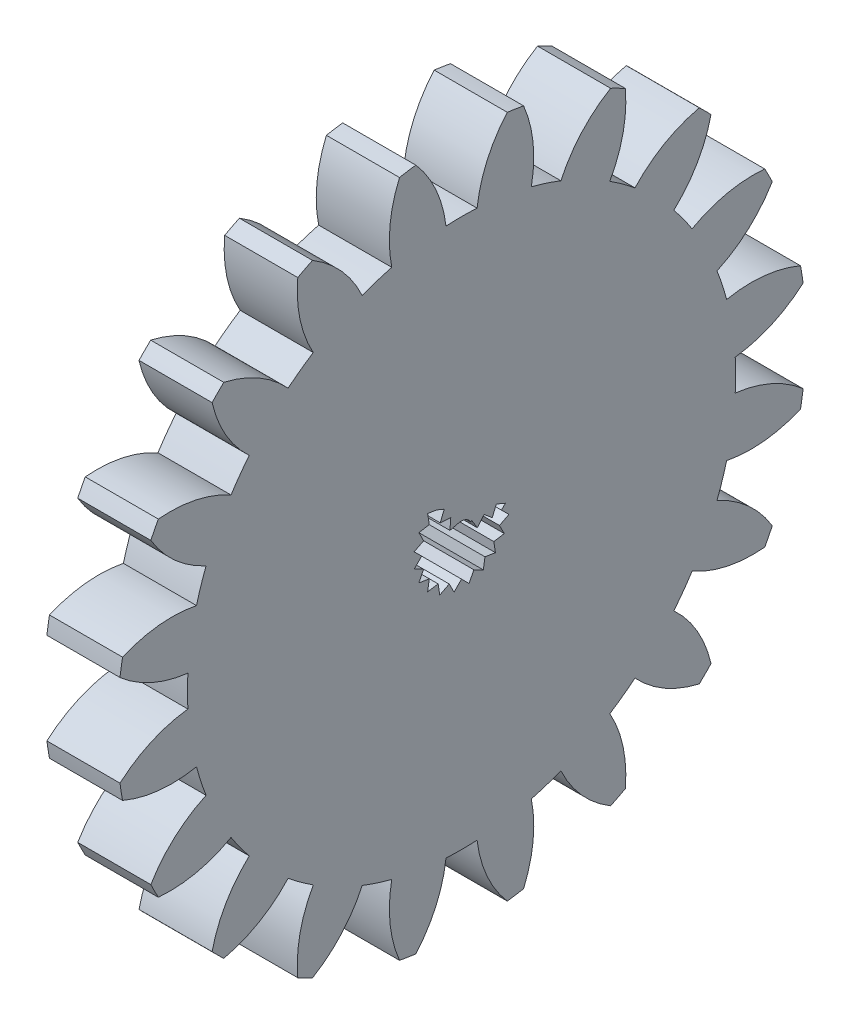
SolidWorks part; units mm, degrees
ref_plane "Plane1" through (0, 0, 0) normal (0, 0, 1) x (1, 0, 0)
ref_plane "Plane2" through (0, 0, 0) normal (0, 1, 0) x (1, 0, 0)
ref_plane "Plane3" through (0, 0, 0) normal (1, 0, 0) x (0, 0, -1)
other "Configuration Table"
sketch "HoldingSke" plane through (0, 0, 0) normal (0, 1, 0) x (1, 0, 0)
  line L0 (0, 0) -> (0.6265, -0.228)
  line L1 (-15, 0) -> (100, 0) construction
  line L2 (0, 0) -> (-2.1039, 2.3779)
  line L3 (0, 0) -> (-11.863, 4.5341)
  line L4 (0, 0) -> (8.1152, 2.9537)
  line L5 (0, 0) -> (-46.8476, -17.4728)
  line L6 (0, 0) -> (-2.9014, -1.9576)
  line L7 (-2.1039, 2.3779) -> (8.6586, 51.2059)
  line L8 (-76.2, 54.61) -> (-76.1, 54.61)
  line L9 (-71.009, 38.7566) -> (-53.1078, 45.2721)
  line L10 (-76.2, 71.12) -> (104.1128, 71.12)
  line L11 (0, 0) -> (-3.5, 0)
  line L12 (-76.2, 101.6) -> (-76.147, 101.6)
  line L13 (24.9733, 27.94) -> (52.9518, 28.4284)
  line L14 (24.9733, 27.94) -> (24.9743, 27.94)
  line L15 (24.9733, 27.94) -> (100.4006, 29.5858)
  line L16 (-63.627, -1.5) -> (-12.827, -1.5)
  circle A0 centre (0, 0) radius 0.5
  circle A1 centre (0, 0) radius 13.124
  circle A2 centre (0, 0) radius 37.5
  circle A3 centre (0, 0) radius 0.5
  dimension "MHD" = 26.248
  dimension "Hub_dia" = 75
  dimension "Bore" = 1
  dimension "MBD" = 1
  dimension "Num_teeth" = 20
  dimension "Pitch" = 0.6667
  dimension "Overall_len" = 50
  dimension "Show_teeth" = 20
  dimension "Thickness" = 3.5
  dimension "OAL" = 50.0001
  dimension "T_dim" = 0.1
  dimension "Ap" = 20
  dimension "H" = 19.05
  dimension "Pitch_radius" = 180.3128
  dimension "Width" = 3.5
  dimension "Backlash" = 0.053
  dimension "Addendum_fac" = 1
  dimension "Dedendum_fac" = 1.25
  dimension "Clearance_fac" = 0.25
  dimension "Dedendum_add" = 0.001
  dimension "Module" = 1.5
sketch "BasProSke" plane through (0, 0, 0) normal (0, 1, 0) x (1, 0, 0)
  line L0 (-10, 0) -> (60, 0) construction
  line L1 (0, 0) -> (0, 16.5)
  line L2 (0, 0) -> (3.5, 0)
  line L3 (3.5, 0) -> (3.5, 16.5)
  line L4 (3.5, 16.5) -> (0, 16.5)
  dimension "Thickness" = 3.5
  dimension "Diameter" = 33
revolve "Base-Revolve" add sketch "BasProSke" angle 360 about L0
sketch "TooCutSke" plane through (0, 0, 0) normal (1, 0, 0) x (0, 0, -1)
  line L1 (0, 0) -> (0, 107) construction
  line L2 (0, 0) -> (-1.2696, 14.9462) construction
  line L3 (0, 0) -> (-4.6808, 29.5532) construction
  line L4 (-1.2696, 14.9462) -> (-2.3404, 14.7766) construction
  arc A0 (0.7438, 13.1029) -> (-0.7438, 13.1029) centre (0, 0) ccw
  arc A1 (2.21, 16.377) -> (-2.21, 16.377) centre (0, 0) ccw
  circle A2 centre (0, 0) radius 15 construction
  circle A3 centre (0, 0) radius 14.0954 construction
  arc A4 (-0.7438, 13.1029) -> (-2.21, 16.377) centre (-6.7025, 12.3999) ccw
  arc A5 (2.21, 16.377) -> (0.7438, 13.1029) centre (6.7025, 12.3999) ccw
  dimension "Root_dia" = 26.248
  dimension "Overcut_dia" = 33.0508
  dimension "Pitch_dia" = 30
  dimension "Base_dia" = 28.1908
  dimension "Flank_rad" = 6
  dimension "Half_ang" = 9
  dimension "Half_CT" = 1.0841
extrude "ToothCut" cut sketch "TooCutSke" along normal through all
fillet "Breaks" [suppressed] radius 0.03
fillet "RootFillets" [suppressed] radius 0.376
pattern_circular "TeethCuts" count 20 every 18 about axis through (-10, 0, 0) along (1, 0, 0) of "ToothCut", "RootFillets", "Breaks"
sketch "HubNeaOneSke" plane through (0, 0, 0) normal (-1, 0, 0) x (0, 0, 1)
  circle A0 centre (0, 0) radius 13.124
  dimension "Diameter" = 26.248
extrude "HubNearOne" [suppressed] add sketch "HubNeaOneSke" along normal blind 46.5001
sketch "HubNeaBotSke" plane through (0, 0, 0) normal (-1, 0, 0) x (0, 0, 1)
  circle A0 centre (0, 0) radius 13.124
  dimension "Diameter" = 26.248
extrude "HubNearBoth" [suppressed] add sketch "HubNeaBotSke" along normal blind 23.25
ref_plane "FarPln" through (3.5, 0, 0) normal (1, 0, 0) x (0, 0, -1)
sketch "HubFarSke" plane through (3.5, 0, 0) normal (1, 0, 0) x (0, 0, -1)
  circle A0 centre (0, 0) radius 13.124
  dimension "Diameter" = 26.248
extrude "HubFar" [suppressed] add sketch "HubFarSke" along normal blind 23.25
sketch "BorSke" plane through (0, 0, 0) normal (1, 0, 0) x (0, 0, -1)
  circle A0 centre (0, 0) radius 0.5
  dimension "Diameter" = 1
extrude "Bore" cut sketch "BorSke" along normal mid plane 100.0001
sketch "KeySke" plane through (0, 0, 0) normal (1, 0, 0) x (0, 0, -1)
  line L0 (-0.05, 0) -> (-0.05, 0.6)
  line L1 (-0.05, 0.6) -> (0.05, 0.6)
  line L2 (0.05, 0.6) -> (0.05, 0)
  line L3 (0, 0) -> (0, 34) construction
  line L4 (-0.05, 0) -> (0.05, 0)
  dimension "Offset" = 0.6
  dimension "Width" = 0.1
extrude "Keyway" [suppressed] cut sketch "KeySke" along normal mid plane 100.0001
pattern_circular "Keyway2" [suppressed] count 2 every 90 about axis through (-10, 0, 0) along (1, 0, 0)
sketch "Sketch1" plane through (0, 0, 0) normal (-1, 0, 0) x (0, 0, 1)
  line L0 (-1.4699, -0.0979) -> (-1.6647, 0.3712) construction
  line L1 (-1.6647, 0.3712) -> (-2.1338, 0.1764) construction
  line L2 (-2.1338, 0.1764) -> (-2.1741, 0.6828) construction
  line L3 (-2.1741, 0.6828) -> (-2.6805, 0.6424) construction
  line L4 (-2.6805, 0.6424) -> (-2.5624, 1.1365) construction
  line L5 (-2.5624, 1.1365) -> (-3.0564, 1.2546) construction
  line L6 (-3.0564, 1.2546) -> (-2.7914, 1.6879) construction
  line L7 (-2.7914, 1.6879) -> (-3.2247, 1.953) construction
  line L8 (-3.2247, 1.953) -> (-2.8388, 2.2832) construction
  line L9 (-2.8388, 2.2832) -> (-3.169, 2.6692) construction
  line L10 (-3.169, 2.6692) -> (-2.6999, 2.864) construction
  line L11 (-2.6999, 2.864) -> (-2.8947, 3.3331) construction
  line L12 (-2.8947, 3.3331) -> (-2.3883, 3.3734) construction
  line L13 (-2.3883, 3.3734) -> (-2.4287, 3.8797) construction
  line L14 (-2.4287, 3.8797) -> (-1.9346, 3.7616) construction
  line L15 (-1.9346, 3.7616) -> (-1.8165, 4.2556) construction
  line L16 (-1.8165, 4.2556) -> (-1.3832, 3.9906) construction
  line L17 (-1.3832, 3.9906) -> (-1.1181, 4.424) construction
  line L18 (-1.1181, 4.424) -> (-0.7879, 4.038) construction
  line L19 (-0.7879, 4.038) -> (-0.402, 4.3682) construction
  line L20 (-0.402, 4.3682) -> (-0.2071, 3.8991) construction
  line L21 (-0.2071, 3.8991) -> (0.262, 4.0939) construction
  line L22 (0.262, 4.0939) -> (0.3023, 3.5876) construction
  line L23 (0.3023, 3.5876) -> (0.8086, 3.6279) construction
  line L24 (0.8086, 3.6279) -> (0.6905, 3.1339) construction
  line L25 (0.6905, 3.1339) -> (1.1845, 3.0157) construction
  line L26 (1.1845, 3.0157) -> (0.9195, 2.5824) construction
  line L27 (0.9195, 2.5824) -> (1.3529, 2.3174) construction
  line L28 (1.3529, 2.3174) -> (0.9669, 1.9871) construction
  line L29 (0.9669, 1.9871) -> (1.2971, 1.6012) construction
  line L30 (1.2971, 1.6012) -> (0.828, 1.4064) construction
  line L31 (0.828, 1.4064) -> (1.0228, 0.9373) construction
  line L32 (1.0228, 0.9373) -> (0.5165, 0.897) construction
  line L33 (0.5165, 0.897) -> (0.5568, 0.3906) construction
  line L34 (0.5568, 0.3906) -> (0.0628, 0.5087) construction
  line L35 (0.0628, 0.5087) -> (-0.0554, 0.0147) construction
  line L36 (-0.0554, 0.0147) -> (-0.4887, 0.2797) construction
  line L37 (-0.4887, 0.2797) -> (-0.7537, -0.1536) construction
  line L38 (-0.7537, -0.1536) -> (-1.084, 0.2323) construction
  line L39 (-1.084, 0.2323) -> (-1.4699, -0.0979) construction
  line L40 (-1.4699, -0.0979) -> (-1.6647, 0.3712)
  line L41 (-1.6647, 0.3712) -> (-2.1338, 0.1764)
  line L42 (-2.1338, 0.1764) -> (-2.1741, 0.6828)
  line L43 (-2.1741, 0.6828) -> (-2.6805, 0.6424)
  line L44 (-2.6805, 0.6424) -> (-2.5624, 1.1365)
  line L45 (-2.5624, 1.1365) -> (-3.0564, 1.2546)
  line L46 (-3.0564, 1.2546) -> (-2.7914, 1.6879)
  line L47 (-2.7914, 1.6879) -> (-3.2247, 1.953)
  line L48 (-3.2247, 1.953) -> (-2.8388, 2.2832)
  line L49 (-2.8388, 2.2832) -> (-3.169, 2.6692)
  line L50 (-3.169, 2.6692) -> (-2.6999, 2.864)
  line L51 (-2.6999, 2.864) -> (-2.8947, 3.3331)
  line L52 (-2.8947, 3.3331) -> (-2.3883, 3.3734)
  line L53 (-2.3883, 3.3734) -> (-2.4287, 3.8797)
  line L54 (-2.4287, 3.8797) -> (-1.9346, 3.7616)
  line L55 (-1.9346, 3.7616) -> (-1.8165, 4.2556)
  line L56 (-1.8165, 4.2556) -> (-1.3832, 3.9906)
  line L57 (-1.3832, 3.9906) -> (-1.1181, 4.424)
  line L58 (-1.1181, 4.424) -> (-0.7879, 4.038)
  line L59 (-0.7879, 4.038) -> (-0.402, 4.3682)
  line L60 (-0.402, 4.3682) -> (-0.2071, 3.8991)
  line L61 (-0.2071, 3.8991) -> (0.262, 4.0939)
  line L62 (0.262, 4.0939) -> (0.3023, 3.5876)
  line L63 (0.3023, 3.5876) -> (0.8086, 3.6279)
  line L64 (0.8086, 3.6279) -> (0.6905, 3.1339)
  line L65 (0.6905, 3.1339) -> (1.1845, 3.0157)
  line L66 (1.1845, 3.0157) -> (0.9195, 2.5824)
  line L67 (0.9195, 2.5824) -> (1.3529, 2.3174)
  line L68 (1.3529, 2.3174) -> (0.9669, 1.9871)
  line L69 (0.9669, 1.9871) -> (1.2971, 1.6012)
  line L70 (1.2971, 1.6012) -> (0.828, 1.4064)
  line L71 (0.828, 1.4064) -> (1.0228, 0.9373)
  line L72 (1.0228, 0.9373) -> (0.5165, 0.897)
  line L73 (0.5165, 0.897) -> (0.5568, 0.3906)
  line L74 (0.5568, 0.3906) -> (0.0628, 0.5087)
  line L75 (0.0628, 0.5087) -> (-0.0554, 0.0147)
  line L76 (-0.0554, 0.0147) -> (-0.4887, 0.2797)
  line L77 (-0.4887, 0.2797) -> (-0.7537, -0.1536)
  line L78 (-0.7537, -0.1536) -> (-1.084, 0.2323)
  line L79 (-1.084, 0.2323) -> (-1.4699, -0.0979)
  line L80 (2.2678, -0.3592) -> (1.9086, 0)
  line L81 (1.9086, 0) -> (2.2678, 0.3592)
  line L82 (2.2678, 0.3592) -> (1.8152, 0.5898)
  line L83 (1.8152, 0.5898) -> (2.0458, 1.0424)
  line L84 (2.0458, 1.0424) -> (1.5441, 1.1218)
  line L85 (1.5441, 1.1218) -> (1.6235, 1.6235)
  line L86 (1.6235, 1.6235) -> (1.1218, 1.5441)
  line L87 (1.1218, 1.5441) -> (1.0424, 2.0458)
  line L88 (1.0424, 2.0458) -> (0.5898, 1.8152)
  line L89 (0.5898, 1.8152) -> (0.3592, 2.2678)
  line L90 (0.3592, 2.2678) -> (0, 1.9086)
  line L91 (0, 1.9086) -> (-0.3592, 2.2678)
  line L92 (-0.3592, 2.2678) -> (-0.5898, 1.8152)
  line L93 (-0.5898, 1.8152) -> (-1.0424, 2.0458)
  line L94 (-1.0424, 2.0458) -> (-1.1218, 1.5441)
  line L95 (-1.1218, 1.5441) -> (-1.6235, 1.6235)
  line L96 (-1.6235, 1.6235) -> (-1.5441, 1.1218)
  line L97 (-1.5441, 1.1218) -> (-2.0458, 1.0424)
  line L98 (-2.0458, 1.0424) -> (-1.8152, 0.5898)
  line L99 (-1.8152, 0.5898) -> (-2.2678, 0.3592)
  line L100 (-2.2678, 0.3592) -> (-1.9086, 0)
  line L101 (-1.9086, 0) -> (-2.2678, -0.3592)
  line L102 (-2.2678, -0.3592) -> (-1.8152, -0.5898)
  line L103 (-1.8152, -0.5898) -> (-2.0458, -1.0424)
  line L104 (-2.0458, -1.0424) -> (-1.5441, -1.1218)
  line L105 (-1.5441, -1.1218) -> (-1.6235, -1.6235)
  line L106 (-1.6235, -1.6235) -> (-1.1218, -1.5441)
  line L107 (-1.1218, -1.5441) -> (-1.0424, -2.0458)
  line L108 (-1.0424, -2.0458) -> (-0.5898, -1.8152)
  line L109 (-0.5898, -1.8152) -> (-0.3592, -2.2678)
  line L110 (-0.3592, -2.2678) -> (0, -1.9086)
  line L111 (0, -1.9086) -> (0.3592, -2.2678)
  line L112 (0.3592, -2.2678) -> (0.5898, -1.8152)
  line L113 (0.5898, -1.8152) -> (1.0424, -2.0458)
  line L114 (1.0424, -2.0458) -> (1.1218, -1.5441)
  line L115 (1.1218, -1.5441) -> (1.6235, -1.6235)
  line L116 (1.6235, -1.6235) -> (1.5441, -1.1218)
  line L117 (1.5441, -1.1218) -> (2.0458, -1.0424)
  line L118 (2.0458, -1.0424) -> (1.8152, -0.5898)
  line L119 (1.8152, -0.5898) -> (2.2678, -0.3592)
  arc A0 (13.1029, 0.7438) -> (16.354, 2.1898) centre (12.3999, 6.7025) ccw construction
  arc A1 (16.354, 2.1898) -> (16.2303, 2.9711) centre (0, 0) ccw construction
  arc A2 (16.2303, 2.9711) -> (12.6915, 3.3416) centre (13.8642, -2.5427) ccw construction
  arc A3 (12.6915, 3.3416) -> (12.2318, 4.7564) centre (0, 0) ccw construction
  arc A4 (12.2318, 4.7564) -> (14.8769, 7.1363) centre (9.7218, 10.2062) ccw construction
  arc A5 (14.8769, 7.1363) -> (14.5178, 7.8411) centre (0, 0) ccw construction
  arc A6 (14.5178, 7.8411) -> (11.0377, 7.0999) centre (13.9713, 1.866) ccw construction
  arc A7 (11.0377, 7.0999) -> (10.1633, 8.3035) centre (0, 0) ccw construction
  arc A8 (10.1633, 8.3035) -> (11.9436, 11.3842) centre (6.0921, 12.7109) ccw construction
  arc A9 (11.9436, 11.3842) -> (11.3842, 11.9436) centre (0, 0) ccw construction
  arc A10 (11.3842, 11.9436) -> (8.3035, 10.1633) centre (12.7109, 6.0921) ccw construction
  arc A11 (8.3035, 10.1633) -> (7.0999, 11.0377) centre (0, 0) ccw construction
  arc A12 (7.0999, 11.0377) -> (7.8411, 14.5178) centre (1.866, 13.9713) ccw construction
  arc A13 (7.8411, 14.5178) -> (7.1363, 14.8769) centre (0, 0) ccw construction
  arc A14 (7.1363, 14.8769) -> (4.7564, 12.2318) centre (10.2062, 9.7218) ccw construction
  arc A15 (4.7564, 12.2318) -> (3.3416, 12.6915) centre (0, 0) ccw construction
  arc A16 (3.3416, 12.6915) -> (2.9711, 16.2303) centre (-2.5427, 13.8642) ccw construction
  arc A17 (2.9711, 16.2303) -> (2.1898, 16.354) centre (0, 0) ccw construction
  arc A18 (2.1898, 16.354) -> (0.7438, 13.1029) centre (6.7025, 12.3999) ccw construction
  arc A19 (0.7438, 13.1029) -> (-0.7438, 13.1029) centre (0, 0) ccw construction
  arc A20 (-0.7438, 13.1029) -> (-2.1898, 16.354) centre (-6.7025, 12.3999) ccw construction
  arc A21 (-2.1898, 16.354) -> (-2.9711, 16.2303) centre (0, 0) ccw construction
  arc A22 (-2.9711, 16.2303) -> (-3.3416, 12.6915) centre (2.5427, 13.8642) ccw construction
  arc A23 (-3.3416, 12.6915) -> (-4.7564, 12.2318) centre (0, 0) ccw construction
  arc A24 (-4.7564, 12.2318) -> (-7.1363, 14.8769) centre (-10.2062, 9.7218) ccw construction
  arc A25 (-7.1363, 14.8769) -> (-7.8411, 14.5178) centre (0, 0) ccw construction
  arc A26 (-7.8411, 14.5178) -> (-7.0999, 11.0377) centre (-1.866, 13.9713) ccw construction
  arc A27 (-7.0999, 11.0377) -> (-8.3035, 10.1633) centre (0, 0) ccw construction
  arc A28 (-8.3035, 10.1633) -> (-11.3842, 11.9436) centre (-12.7109, 6.0921) ccw construction
  arc A29 (-11.3842, 11.9436) -> (-11.9436, 11.3842) centre (0, 0) ccw construction
  arc A30 (-11.9436, 11.3842) -> (-10.1633, 8.3035) centre (-6.0921, 12.7109) ccw construction
  arc A31 (-10.1633, 8.3035) -> (-11.0377, 7.0999) centre (0, 0) ccw construction
  arc A32 (-11.0377, 7.0999) -> (-14.5178, 7.8411) centre (-13.9713, 1.866) ccw construction
  arc A33 (-14.5178, 7.8411) -> (-14.8769, 7.1363) centre (0, 0) ccw construction
  arc A34 (-14.8769, 7.1363) -> (-12.2318, 4.7564) centre (-9.7218, 10.2062) ccw construction
  arc A35 (-12.2318, 4.7564) -> (-12.6915, 3.3416) centre (0, 0) ccw construction
  arc A36 (-12.6915, 3.3416) -> (-16.2303, 2.9711) centre (-13.8642, -2.5427) ccw construction
  arc A37 (-16.2303, 2.9711) -> (-16.354, 2.1898) centre (0, 0) ccw construction
  arc A38 (-16.354, 2.1898) -> (-13.1029, 0.7438) centre (-12.3999, 6.7025) ccw construction
  arc A39 (-13.1029, 0.7438) -> (-13.1029, -0.7438) centre (0, 0) ccw construction
  arc A40 (-13.1029, -0.7438) -> (-16.354, -2.1898) centre (-12.3999, -6.7025) ccw construction
  arc A41 (-16.354, -2.1898) -> (-16.2303, -2.9711) centre (0, 0) ccw construction
  arc A42 (-16.2303, -2.9711) -> (-12.6915, -3.3416) centre (-13.8642, 2.5427) ccw construction
  arc A43 (-12.6915, -3.3416) -> (-12.2318, -4.7564) centre (0, 0) ccw construction
  arc A44 (-12.2318, -4.7564) -> (-14.8769, -7.1363) centre (-9.7218, -10.2062) ccw construction
  arc A45 (-14.8769, -7.1363) -> (-14.5178, -7.8411) centre (0, 0) ccw construction
  arc A46 (-14.5178, -7.8411) -> (-11.0377, -7.0999) centre (-13.9713, -1.866) ccw construction
  arc A47 (-11.0377, -7.0999) -> (-10.1633, -8.3035) centre (0, 0) ccw construction
  arc A48 (-10.1633, -8.3035) -> (-11.9436, -11.3842) centre (-6.0921, -12.7109) ccw construction
  arc A49 (-11.9436, -11.3842) -> (-11.3842, -11.9436) centre (0, 0) ccw construction
  arc A50 (-11.3842, -11.9436) -> (-8.3035, -10.1633) centre (-12.7109, -6.0921) ccw construction
  arc A51 (-8.3035, -10.1633) -> (-7.0999, -11.0377) centre (0, 0) ccw construction
  arc A52 (-7.0999, -11.0377) -> (-7.8411, -14.5178) centre (-1.866, -13.9713) ccw construction
  arc A53 (-7.8411, -14.5178) -> (-7.1363, -14.8769) centre (0, 0) ccw construction
  arc A54 (-7.1363, -14.8769) -> (-4.7564, -12.2318) centre (-10.2062, -9.7218) ccw construction
  arc A55 (-4.7564, -12.2318) -> (-3.3416, -12.6915) centre (0, 0) ccw construction
  arc A56 (-3.3416, -12.6915) -> (-2.9711, -16.2303) centre (2.5427, -13.8642) ccw construction
  arc A57 (-2.9711, -16.2303) -> (-2.1898, -16.354) centre (0, 0) ccw construction
  arc A58 (-2.1898, -16.354) -> (-0.7438, -13.1029) centre (-6.7025, -12.3999) ccw construction
  arc A59 (-0.7438, -13.1029) -> (0.7438, -13.1029) centre (0, 0) ccw construction
  arc A60 (0.7438, -13.1029) -> (2.1898, -16.354) centre (6.7025, -12.3999) ccw construction
  arc A61 (2.1898, -16.354) -> (2.9711, -16.2303) centre (0, 0) ccw construction
  arc A62 (2.9711, -16.2303) -> (3.3416, -12.6915) centre (-2.5427, -13.8642) ccw construction
  arc A63 (3.3416, -12.6915) -> (4.7564, -12.2318) centre (0, 0) ccw construction
  arc A64 (4.7564, -12.2318) -> (7.1363, -14.8769) centre (10.2062, -9.7218) ccw construction
  arc A65 (7.1363, -14.8769) -> (7.8411, -14.5178) centre (0, 0) ccw construction
  arc A66 (7.8411, -14.5178) -> (7.0999, -11.0377) centre (1.866, -13.9713) ccw construction
  arc A67 (7.0999, -11.0377) -> (8.3035, -10.1633) centre (0, 0) ccw construction
  arc A68 (8.3035, -10.1633) -> (11.3842, -11.9436) centre (12.7109, -6.0921) ccw construction
  arc A69 (11.3842, -11.9436) -> (11.9436, -11.3842) centre (0, 0) ccw construction
  arc A70 (11.9436, -11.3842) -> (10.1633, -8.3035) centre (6.0921, -12.7109) ccw construction
  arc A71 (10.1633, -8.3035) -> (11.0377, -7.0999) centre (0, 0) ccw construction
  arc A72 (11.0377, -7.0999) -> (14.5178, -7.8411) centre (13.9713, -1.866) ccw construction
  arc A73 (14.5178, -7.8411) -> (14.8769, -7.1363) centre (0, 0) ccw construction
  arc A74 (14.8769, -7.1363) -> (12.2318, -4.7564) centre (9.7218, -10.2062) ccw construction
  arc A75 (12.2318, -4.7564) -> (12.6915, -3.3416) centre (0, 0) ccw construction
  arc A76 (12.6915, -3.3416) -> (16.2303, -2.9711) centre (13.8642, 2.5427) ccw construction
  arc A77 (16.2303, -2.9711) -> (16.354, -2.1898) centre (0, 0) ccw construction
  arc A78 (16.354, -2.1898) -> (13.1029, -0.7438) centre (12.3999, -6.7025) ccw construction
  arc A79 (13.1029, -0.7438) -> (13.1029, 0.7438) centre (0, 0) ccw construction
  arc A80 (13.1029, 0.7438) -> (16.354, 2.1898) centre (12.3999, 6.7025) ccw
  arc A81 (16.354, 2.1898) -> (16.2303, 2.9711) centre (0, 0) ccw
  arc A82 (16.2303, 2.9711) -> (12.6915, 3.3416) centre (13.8642, -2.5427) ccw
  arc A83 (12.6915, 3.3416) -> (12.2318, 4.7564) centre (0, 0) ccw
  arc A84 (12.2318, 4.7564) -> (14.8769, 7.1363) centre (9.7218, 10.2062) ccw
  arc A85 (14.8769, 7.1363) -> (14.5178, 7.8411) centre (0, 0) ccw
  arc A86 (14.5178, 7.8411) -> (11.0377, 7.0999) centre (13.9713, 1.866) ccw
  arc A87 (11.0377, 7.0999) -> (10.1633, 8.3035) centre (0, 0) ccw
  arc A88 (10.1633, 8.3035) -> (11.9436, 11.3842) centre (6.0921, 12.7109) ccw
  arc A89 (11.9436, 11.3842) -> (11.3842, 11.9436) centre (0, 0) ccw
  arc A90 (11.3842, 11.9436) -> (8.3035, 10.1633) centre (12.7109, 6.0921) ccw
  arc A91 (8.3035, 10.1633) -> (7.0999, 11.0377) centre (0, 0) ccw
  arc A92 (7.0999, 11.0377) -> (7.8411, 14.5178) centre (1.866, 13.9713) ccw
  arc A93 (7.8411, 14.5178) -> (7.1363, 14.8769) centre (0, 0) ccw
  arc A94 (7.1363, 14.8769) -> (4.7564, 12.2318) centre (10.2062, 9.7218) ccw
  arc A95 (4.7564, 12.2318) -> (3.3416, 12.6915) centre (0, 0) ccw
  arc A96 (3.3416, 12.6915) -> (2.9711, 16.2303) centre (-2.5427, 13.8642) ccw
  arc A97 (2.9711, 16.2303) -> (2.1898, 16.354) centre (0, 0) ccw
  arc A98 (2.1898, 16.354) -> (0.7438, 13.1029) centre (6.7025, 12.3999) ccw
  arc A99 (0.7438, 13.1029) -> (-0.7438, 13.1029) centre (0, 0) ccw
  arc A100 (-0.7438, 13.1029) -> (-2.1898, 16.354) centre (-6.7025, 12.3999) ccw
  arc A101 (-2.1898, 16.354) -> (-2.9711, 16.2303) centre (0, 0) ccw
  arc A102 (-2.9711, 16.2303) -> (-3.3416, 12.6915) centre (2.5427, 13.8642) ccw
  arc A103 (-3.3416, 12.6915) -> (-4.7564, 12.2318) centre (0, 0) ccw
  arc A104 (-4.7564, 12.2318) -> (-7.1363, 14.8769) centre (-10.2062, 9.7218) ccw
  arc A105 (-7.1363, 14.8769) -> (-7.8411, 14.5178) centre (0, 0) ccw
  arc A106 (-7.8411, 14.5178) -> (-7.0999, 11.0377) centre (-1.866, 13.9713) ccw
  arc A107 (-7.0999, 11.0377) -> (-8.3035, 10.1633) centre (0, 0) ccw
  arc A108 (-8.3035, 10.1633) -> (-11.3842, 11.9436) centre (-12.7109, 6.0921) ccw
  arc A109 (-11.3842, 11.9436) -> (-11.9436, 11.3842) centre (0, 0) ccw
  arc A110 (-11.9436, 11.3842) -> (-10.1633, 8.3035) centre (-6.0921, 12.7109) ccw
  arc A111 (-10.1633, 8.3035) -> (-11.0377, 7.0999) centre (0, 0) ccw
  arc A112 (-11.0377, 7.0999) -> (-14.5178, 7.8411) centre (-13.9713, 1.866) ccw
  arc A113 (-14.5178, 7.8411) -> (-14.8769, 7.1363) centre (0, 0) ccw
  arc A114 (-14.8769, 7.1363) -> (-12.2318, 4.7564) centre (-9.7218, 10.2062) ccw
  arc A115 (-12.2318, 4.7564) -> (-12.6915, 3.3416) centre (0, 0) ccw
  arc A116 (-12.6915, 3.3416) -> (-16.2303, 2.9711) centre (-13.8642, -2.5427) ccw
  arc A117 (-16.2303, 2.9711) -> (-16.354, 2.1898) centre (0, 0) ccw
  arc A118 (-16.354, 2.1898) -> (-13.1029, 0.7438) centre (-12.3999, 6.7025) ccw
  arc A119 (-13.1029, 0.7438) -> (-13.1029, -0.7438) centre (0, 0) ccw
  arc A120 (-13.1029, -0.7438) -> (-16.354, -2.1898) centre (-12.3999, -6.7025) ccw
  arc A121 (-16.354, -2.1898) -> (-16.2303, -2.9711) centre (0, 0) ccw
  arc A122 (-16.2303, -2.9711) -> (-12.6915, -3.3416) centre (-13.8642, 2.5427) ccw
  arc A123 (-12.6915, -3.3416) -> (-12.2318, -4.7564) centre (0, 0) ccw
  arc A124 (-12.2318, -4.7564) -> (-14.8769, -7.1363) centre (-9.7218, -10.2062) ccw
  arc A125 (-14.8769, -7.1363) -> (-14.5178, -7.8411) centre (0, 0) ccw
  arc A126 (-14.5178, -7.8411) -> (-11.0377, -7.0999) centre (-13.9713, -1.866) ccw
  arc A127 (-11.0377, -7.0999) -> (-10.1633, -8.3035) centre (0, 0) ccw
  arc A128 (-10.1633, -8.3035) -> (-11.9436, -11.3842) centre (-6.0921, -12.7109) ccw
  arc A129 (-11.9436, -11.3842) -> (-11.3842, -11.9436) centre (0, 0) ccw
  arc A130 (-11.3842, -11.9436) -> (-8.3035, -10.1633) centre (-12.7109, -6.0921) ccw
  arc A131 (-8.3035, -10.1633) -> (-7.0999, -11.0377) centre (0, 0) ccw
  arc A132 (-7.0999, -11.0377) -> (-7.8411, -14.5178) centre (-1.866, -13.9713) ccw
  arc A133 (-7.8411, -14.5178) -> (-7.1363, -14.8769) centre (0, 0) ccw
  arc A134 (-7.1363, -14.8769) -> (-4.7564, -12.2318) centre (-10.2062, -9.7218) ccw
  arc A135 (-4.7564, -12.2318) -> (-3.3416, -12.6915) centre (0, 0) ccw
  arc A136 (-3.3416, -12.6915) -> (-2.9711, -16.2303) centre (2.5427, -13.8642) ccw
  arc A137 (-2.9711, -16.2303) -> (-2.1898, -16.354) centre (0, 0) ccw
  arc A138 (-2.1898, -16.354) -> (-0.7438, -13.1029) centre (-6.7025, -12.3999) ccw
  arc A139 (-0.7438, -13.1029) -> (0.7438, -13.1029) centre (0, 0) ccw
  arc A140 (0.7438, -13.1029) -> (2.1898, -16.354) centre (6.7025, -12.3999) ccw
  arc A141 (2.1898, -16.354) -> (2.9711, -16.2303) centre (0, 0) ccw
  arc A142 (2.9711, -16.2303) -> (3.3416, -12.6915) centre (-2.5427, -13.8642) ccw
  arc A143 (3.3416, -12.6915) -> (4.7564, -12.2318) centre (0, 0) ccw
  arc A144 (4.7564, -12.2318) -> (7.1363, -14.8769) centre (10.2062, -9.7218) ccw
  arc A145 (7.1363, -14.8769) -> (7.8411, -14.5178) centre (0, 0) ccw
  arc A146 (7.8411, -14.5178) -> (7.0999, -11.0377) centre (1.866, -13.9713) ccw
  arc A147 (7.0999, -11.0377) -> (8.3035, -10.1633) centre (0, 0) ccw
  arc A148 (8.3035, -10.1633) -> (11.3842, -11.9436) centre (12.7109, -6.0921) ccw
  arc A149 (11.3842, -11.9436) -> (11.9436, -11.3842) centre (0, 0) ccw
  arc A150 (11.9436, -11.3842) -> (10.1633, -8.3035) centre (6.0921, -12.7109) ccw
  arc A151 (10.1633, -8.3035) -> (11.0377, -7.0999) centre (0, 0) ccw
  arc A152 (11.0377, -7.0999) -> (14.5178, -7.8411) centre (13.9713, -1.866) ccw
  arc A153 (14.5178, -7.8411) -> (14.8769, -7.1363) centre (0, 0) ccw
  arc A154 (14.8769, -7.1363) -> (12.2318, -4.7564) centre (9.7218, -10.2062) ccw
  arc A155 (12.2318, -4.7564) -> (12.6915, -3.3416) centre (0, 0) ccw
  arc A156 (12.6915, -3.3416) -> (16.2303, -2.9711) centre (13.8642, 2.5427) ccw
  arc A157 (16.2303, -2.9711) -> (16.354, -2.1898) centre (0, 0) ccw
  arc A158 (16.354, -2.1898) -> (13.1029, -0.7438) centre (12.3999, -6.7025) ccw
  arc A159 (13.1029, -0.7438) -> (13.1029, 0.7438) centre (0, 0) ccw
  circle A160 centre (0, 0) radius 2.296
  point P159 (0, 0)
  point P162 (0, 0)
  point P163 (0, 0)
  point P164 (0, 0)
extrude "Cut-Extrude1" cut sketch "Sketch1" against normal blind 10 contours L118 L119 L80 L81 L82 L83 L84 L85 L86 L87 L88 L89 L90 L91 L92 L93 L94 L95 L96 L97 L98 L99 L100 L101 L102 L103 L104 L105 L106 L107 L108 L109 L110 L111 L112 L113 L114 L115 L116 L117
equation "' \"Module@HoldingSke\" = 6.35"
equation "' \"Num_teeth@HoldingSke\" = 12"
equation "' \"Ap@HoldingSke\" =  20"
equation "' \"Ap@HoldingSke\" = 20"
equation "' \"Width@HoldingSke\" = 0.5 * 25.4"
equation "' \"Hub_dia@HoldingSke\"= 1 * 25.4"
equation "' \"Hub_dia@HoldingSke\" = 1 * 25.4"
equation "' \"Overall_len@HoldingSke\" = 1.0 * 25.4"
equation "' \"Bore@HoldingSke\" = 0.75 * 25.4"
equation "' \"T_dim@HoldingSke\" = 0.1 * 25.4"
equation "' \"Width@KeySke\" = 0.25 * 25.4"
equation "' \"Show_teeth@HoldingSke\" = 13"
equation "' \"Backlash@HoldingSke\" = 0.009 * 25.4"
equation "' \"Addendum_fac@HoldingSke\" = 1.0"
equation "' \"Dedendum_fac@HoldingSke\" = 1.25"
equation "' \"Dedendum_add@HoldingSke\" = 0.00005 * 25.4"
equation "' \"Clearance_fac@HoldingSke\" = 0.25"
equation "\"Pitch@HoldingSke\" = 1 / \"Module@HoldingSke\""
equation "\"Overcut_dia@TooCutSke\" = (\"Num_teeth@HoldingSke\" + 2 * \"Addendum_fac@HoldingSke\") / \"Pitch@HoldingSke\" + 0.002 * 25.4"
equation "\"Pitch_dia@TooCutSke\" = \"Num_teeth@HoldingSke\" / \"Pitch@HoldingSke\""
equation "\"Base_dia@TooCutSke\" = \"Num_teeth@HoldingSke\" / \"Pitch@HoldingSke\" * cos((\"Ap@HoldingSke\"  * 3.14159265 / 180))"
equation "\"Root_dia@TooCutSke\" = (\"Num_teeth@HoldingSke\" + 2) / \"Pitch@HoldingSke\" - 2 * (\"Addendum_fac@HoldingSke\" + \"Dedendum_fac@HoldingSke\") / \"Pitch@HoldingSke\" - \"Dedendum_add@HoldingSke\" * 2"
equation "\"Half_ang@TooCutSke\" = 180 / \"Num_teeth@HoldingSke\""
equation "\"Half_CT@TooCutSke\" = \"Num_teeth@HoldingSke\" / \"Pitch@HoldingSke\" * sin((3.14159265 / 2 / \"Num_teeth@HoldingSke\")) / 2 - 7 * \"Backlash@HoldingSke\" / 4"
equation "\"Flank_rad@TooCutSke\" = \"Num_teeth@HoldingSke\" / \"Pitch@HoldingSke\" / 5"
equation "\"Radius@RootFillets\" = \"Clearance_fac@HoldingSke\" / \"Pitch@HoldingSke\" + \"Dedendum_add@HoldingSke\""
equation "\"Break_rad@Breaks\" = 0.02 / \"Pitch@HoldingSke\""
equation "\"Thickness@HoldingSke\" = \"Width@HoldingSke\""
equation "\"OAL@HoldingSke\" = \"Thickness@HoldingSke\""
equation "\"MHD@HoldingSke\" = (\"Num_teeth@HoldingSke\" + 2) / \"Pitch@HoldingSke\" - 2 * (\"Addendum_fac@HoldingSke\" + \"Dedendum_fac@HoldingSke\")  / \"Pitch@HoldingSke\" - \"Dedendum_add@HoldingSke\" * 2"
equation "\"MBD@HoldingSke\" = (\"Num_teeth@HoldingSke\" + 2) / \"Pitch@HoldingSke\" - 2 * (\"Addendum_fac@HoldingSke\" + \"Dedendum_fac@HoldingSke\")  / \"Pitch@HoldingSke\" - \"Dedendum_add@HoldingSke\" * 2 - 0.002 * 25.4"
equation "\"MHD@HoldingSke\" = ((sgn( \"MHD@HoldingSke\" - \"Hub_dia@HoldingSke\" )-1)*( \"MHD@HoldingSke\" - \"Hub_dia@HoldingSke\" ))/-2+ \"Hub_dia@HoldingSke\""
equation "\"MBD@HoldingSke\" = ((sgn( \"MBD@HoldingSke\" - \"Bore@HoldingSke\" )-1)*( \"MBD@HoldingSke\" - \"Bore@HoldingSke\" ))/-2+ \"Bore@HoldingSke\""
equation "\"OAL@HoldingSke\" = ((sgn( \"OAL@HoldingSke\" - \"Overall_len@HoldingSke\" )+1)*( \"OAL@HoldingSke\" - \"Overall_len@HoldingSke\" ))/2 + \"Overall_len@HoldingSke\" + 0.000002 * 25.4"
equation "\"Num_teeth@TeethCuts\" = int( \"Show_teeth@HoldingSke\" ) + 1"
equation "\"Num_teeth@TeethCuts\" = ((sgn( \"Num_teeth@TeethCuts\" - \"Num_teeth@HoldingSke\" )-1)*( \"Num_teeth@TeethCuts\" - \"Num_teeth@HoldingSke\" ))/-2+ \"Num_teeth@HoldingSke\""
equation "\"Num_teeth@TeethCuts\" = ((sgn( \"Num_teeth@TeethCuts\" - 2.0)+1)*( \"Num_teeth@TeethCuts\" - 2.0))/2 +2.0"
equation "\"Angle@TeethCuts\" = 360.0 / \"Num_teeth@HoldingSke\""
equation "\"Diameter@BasProSke\" = (\"Num_teeth@HoldingSke\" + 2 * \"Addendum_fac@HoldingSke\") / \"Pitch@HoldingSke\""
equation "\"Thickness@BasProSke\"  = \"Thickness@HoldingSke\""
equation "' \"Fillet_rad@BasProSke\" =  \"Thickness@HoldingSke\" * 0.05"
equation "' \"Fillet_rad@BasProSke\" = \"Thickness@HoldingSke\" * 0.05"
equation "\"MHD@HoldingSke\" = ((sgn( \"MHD@HoldingSke\" - \"Root_dia@TooCutSke\" )-1)*( \"MHD@HoldingSke\" - \"Root_dia@TooCutSke\" ))/-2+ \"Root_dia@TooCutSke\""
equation "\"Diameter@HubNeaOneSke\" = \"MHD@HoldingSke\""
equation "\"Length@HubNearOne\" = \"OAL@HoldingSke\" - \"Thickness@BasProSke\""
equation "\"Diameter@HubNeaBotSke\" = \"MHD@HoldingSke\""
equation "\"Length@HubNearBoth\" = ( \"OAL@HoldingSke\" - \"Thickness@BasProSke\" ) / 2.0"
equation "\"Thickness@FarPln\" = \"Thickness@BasProSke\""
equation "\"Diameter@HubFarSke\" = \"MHD@HoldingSke\""
equation "\"Length@HubFar\" = ( \"OAL@HoldingSke\" - \"Thickness@BasProSke\" ) / 2.0"
equation "\"Diameter@BorSke\" = \"MBD@HoldingSke\""
equation "\"D1@Bore\" = \"OAL@HoldingSke\" * 2.0"
equation "\"D1@Keyway\" = \"OAL@HoldingSke\" * 2.0"
equation "\"Offset@KeySke\" = \"T_dim@HoldingSke\" + \"MBD@HoldingSke\" / 2.0"
